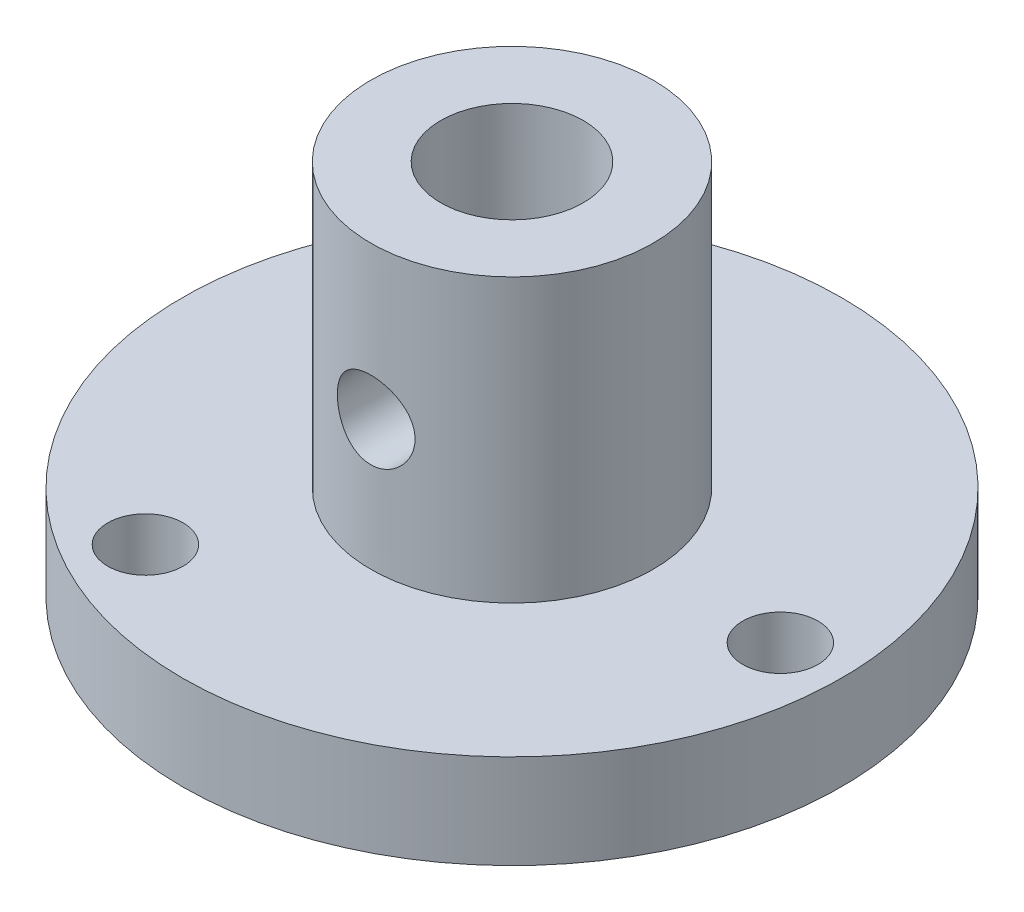
SolidWorks part; units mm, degrees
ref_plane "Plan de face" through (0, 0, 0) normal (0, 0, 1) x (1, 0, 0)
ref_plane "Plan de dessus" through (0, 0, 0) normal (0, 1, 0) x (1, 0, 0)
ref_plane "Plan de droite" through (0, 0, 0) normal (1, 0, 0) x (0, 0, -1)
sketch "Esquisse1" plane through (0, 0, 0) normal (0, 0, 1) x (1, 0, 0)
  line L0 (-3.03, 0) -> (-3.03, 16)
  line L1 (-3.03, 16) -> (-6, 16)
  line L2 (-6, 16) -> (-6, 4)
  line L3 (-6, 4) -> (-14, 4)
  line L4 (-14, 4) -> (-14, 0)
  line L5 (-14, 0) -> (-3.03, 0)
  line L6 (0, 0) -> (0, 17.0847) construction
  dimension "D1" = 4
  dimension "D2" = 16
  dimension "D3" = 3.03
  dimension "D4" = 6
  dimension "D5" = 14
revolve "Révolution1" add sketch "Esquisse1" angle 360 about L6
sketch "Esquisse2" plane through (0, 0, 0) normal (0, -1, 0) x (1, 0, 0)
  circle A0 centre (0, 0) radius 11.4 construction
  circle A1 centre (11.4, 0) radius 1.6
  circle A2 centre (-5.7, -9.8727) radius 1.6
  circle A3 centre (-5.7, 9.8727) radius 1.6
  point P5 (-4.4784, 11.9877)
  point P6 (0, 0)
  point P11 (0, 0)
  dimension "D1" = 22.8
  dimension "D2" = 3.2
  dimension "D3" = 3
extrude "Enlèv. mat.-Extru.1" cut sketch "Esquisse2" against normal through all
ref_plane "Plan1" through (0, 0, 6) normal (0, 0, 1) x (1, 0, 0)
sketch "Esquisse3" plane through (0, 0, 6) normal (0, 0, 1) x (1, 0, 0)
  line L0 (0, 16) -> (0, 0) construction
  line L1 (6, 16) -> (-6, 16) construction
  line L2 (14, 4) -> (-14, 4) construction
  circle A0 centre (0, 9.5) radius 1.65
  dimension "D1" = 3.3
  dimension "D2" = 5.5
extrude "Enlèv. mat.-Extru.2" cut sketch "Esquisse3" against normal through all
